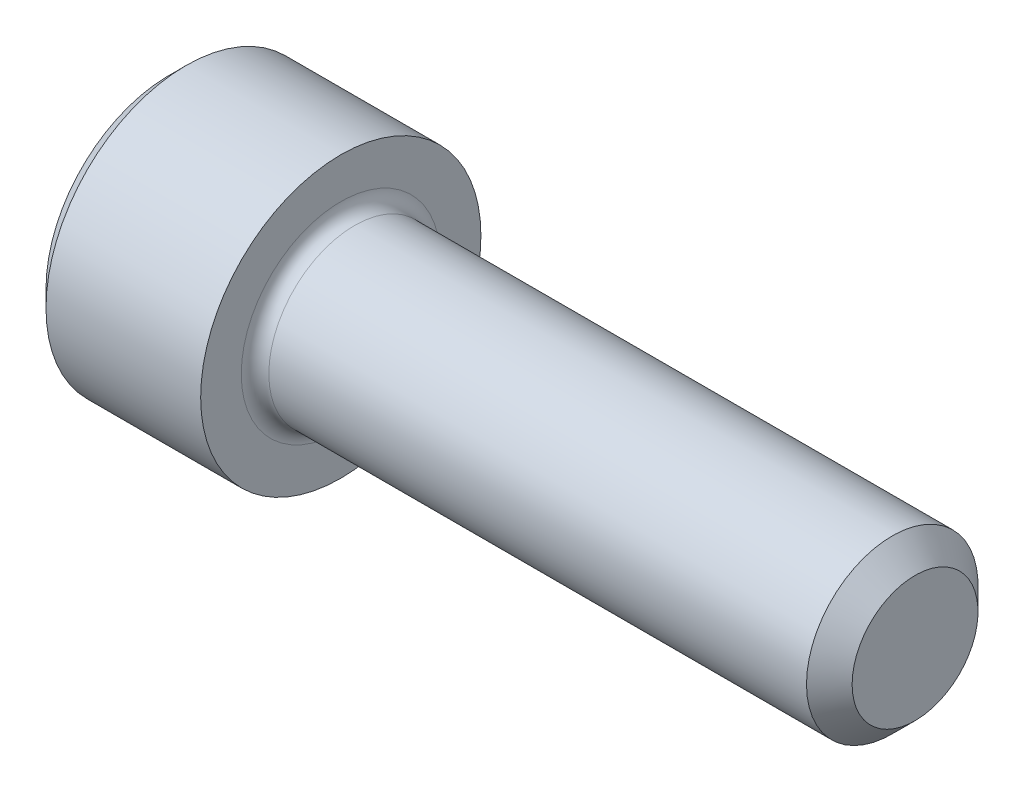
SolidWorks part; units mm, degrees
revolve "Base-Revolve" add sketch "BodySke"
sketch "BodySke" plane through (0, 0, 0) normal (0, 0, 1) x (1, 0, 0)
  line L0 (0, 0) -> (0, 2.0447)
  line L1 (0.2794, 2.3241) -> (2.8448, 2.3241)
  line L2 (2.8448, 2.3241) -> (2.8448, 1.4224)
  line L3 (2.8448, 1.4224) -> (11.9913, 1.4224)
  line L4 (12.3698, 1.0439) -> (12.3698, 0)
  line L5 (12.3698, 0) -> (0, 0)
  line L6 (-31.75, 0) -> (127, 0) construction
  line L7 (0, 2.0447) -> (0.2794, 2.3241)
  line L8 (12.3698, 1.0439) -> (11.9913, 1.4224)
  line L9 (0, -2.0447) -> (0.2794, -2.3241) construction
  line L10 (12.3698, -1.0439) -> (11.9913, -1.4224) construction
  line L11 (3.4798, 9.525) -> (3.4798, 3.175) construction
  line L12 (2.8448, 9.525) -> (2.8448, 3.175) construction
  line L13 (-25.7302, 9.525) -> (-25.7302, 3.175) construction
  dimension "Diameter" = 2.8448
  dimension "Head_ht" = 2.8448
  dimension "Length" = 9.525
  dimension "Body_ch_ang" = 45
  dimension "Head_dia" = 4.6482
  dimension "Head_ch_ang" = 45
  dimension "Head_side_ht" = 2.5654
  dimension "Minor_dia" = 2.0879
  dimension "Advance" = 0.635
  dimension "Thread_nom" = 9.525
  dimension "Thread_length" = 38.1
cosmetic thread "ThreadCosmetic"
fillet "Fillet1" radius 0.2286 1 edges at (2.8448, 0, 1.4224)
material "Alloy Steel"
ref_plane "Plane1" through (0, 0, 0) normal (0, 0, 1) x (1, 0, 0)
ref_plane "Plane2" through (0, 0, 0) normal (0, 1, 0) x (1, 0, 0)
ref_plane "Plane3" through (0, 0, 0) normal (1, 0, 0) x (0, 0, -1)
sketch "Sketch2" plane through (0, 0, 0) normal (0, 0, 1) x (1, 0, 0)
  line L0 (0, 1.1938) -> (1.2954, 1.1938)
  line L1 (1.2954, 1.1938) -> (1.9846, 0)
  line L2 (-31.75, 0) -> (127, 0) construction
  line L3 (1.9846, 0) -> (0, 0)
  line L4 (0, 0) -> (0, 1.1938)
  line L5 (0, 2.0447) -> (0, -2.0447) construction
  line L6 (0, 0) -> (47.625, 0) construction
  line L7 (2.8448, -2.3241) -> (2.8448, 2.3241) construction
  dimension "D1" = 1.1938
  dimension "D2" = 60
revolve "Hex-PreBroach" cut sketch "Sketch2" angle 360 about L6
sketch "Sketch3" plane through (0, 0, 0) normal (-1, 0, 0) x (0, 0.5, 0.866)
  line L0 (0.6892, 1.1938) -> (-0.6892, 1.1938)
  line L1 (-0.6892, 1.1938) -> (-1.3785, 0)
  line L2 (0.6892, 1.1938) -> (1.3785, 0)
  line L3 (0.6892, -1.1938) -> (1.3785, 0)
  line L4 (0.6892, -1.1938) -> (-0.6892, -1.1938)
  line L5 (-0.6892, -1.1938) -> (-1.3785, 0)
  dimension "D1" = 1.1938
  dimension "D2" = 1.1938
  dimension "Hex_size" = 2.3876
extrude "Hex" cut sketch "Sketch3" against normal blind 1.2954
equation "\"D2@Sketch3\" = \"Hex_size@Sketch3\" / 2"
equation "\"D1@Sketch3\" = \"Hex_size@Sketch3\" / 2"
equation "\"D1@Sketch2\" = \"Hex_size@Sketch3\" / 2"
equation "\"Thread_minor@ThreadCosmetic\"  =  \"Minor_dia@BodySke\""
equation "\"Wall_thickness@Sketch2\" = \"Head_ht@BodySke\" - \"Key_eng@Hex\""
equation "\"Thread_length@ThreadCosmetic\" = ((sgn( (\"Length@BodySke\" - \"Advance@BodySke\" ) - \"Thread_nom@BodySke\" )-1)*( (\"Length@BodySke\" - \"Advance@BodySke\" ) - \"Thread_nom@BodySke\" ))/-2+ \"Thread_nom@BodySke\""
